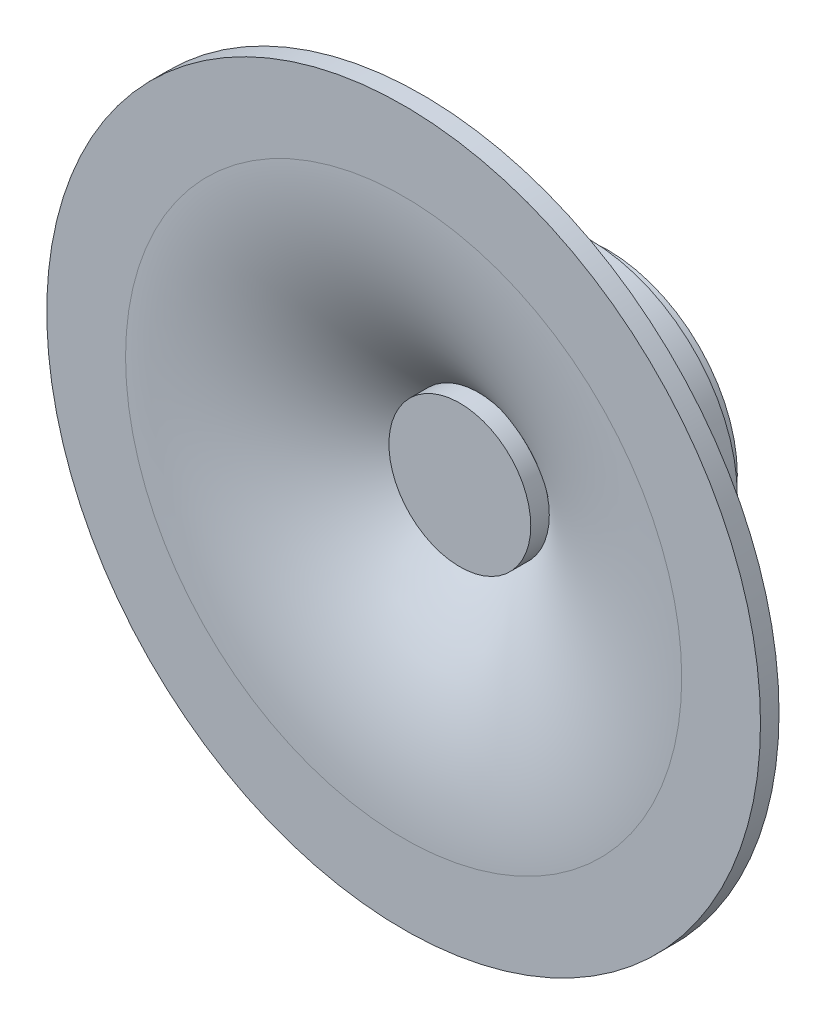
SolidWorks part; units mm, degrees
ref_plane "Front Plane" through (0, 0, 0) normal (0, 0, 1) x (1, 0, 0)
ref_plane "Top Plane" through (0, 0, 0) normal (0, 1, 0) x (1, 0, 0)
ref_plane "Right Plane" through (0, 0, 0) normal (1, 0, 0) x (0, 0, -1)
sketch "Sketch1" plane through (0, 0, 0) normal (1, 0, 0) x (0, 0, -1)
  line L0 (0, 0) -> (20, 0) construction
  line L1 (20, 0) -> (20, 14)
  line L2 (20, 14) -> (18, 14)
  line L3 (18, 14) -> (18, 16)
  line L4 (18, 16) -> (12, 16)
  line L5 (12, 16) -> (12, 14)
  line L6 (12, 14) -> (10, 14)
  line L7 (0, 0) -> (0, 35) construction
  line L8 (10, 14) -> (5.5, 14) construction
  line L9 (5.5, 14) -> (5.5, 18.25) construction
  line L10 (7.5, 18.0311) -> (0, 35)
  line L11 (0, 35) -> (0, 38.5)
  line L12 (0, 38.5) -> (-2, 38.5)
  line L13 (-2, 38.5) -> (-2, 30)
  line L14 (6.0653, 7.65) -> (4.0653, 7.65)
  line L15 (4.0653, 7.65) -> (4.0653, 0)
  line L16 (4.0653, 0) -> (20, 0)
  arc A0 (10, 14) -> (7.5, 18.0311) centre (5.5, 14) ccw
  arc A1 (-2, 30) -> (6.0653, 7.65) centre (33, 30) ccw
  dimension "D15" = 35
  dimension "D1" = 14
  dimension "D2" = 20
  dimension "D3" = 2
  dimension "D4" = 32
  dimension "D5" = 6
  dimension "D6" = 4.5
  dimension "D7" = 36.5
  dimension "D8" = 70
  dimension "D9" = 2
  dimension "D10" = 77
  dimension "D11" = 2
  dimension "D12" = 60
  dimension "D13" = 15.3
  dimension "D14" = 2
revolve "Revolve1" add sketch "Sketch1" angle 360 about L16
